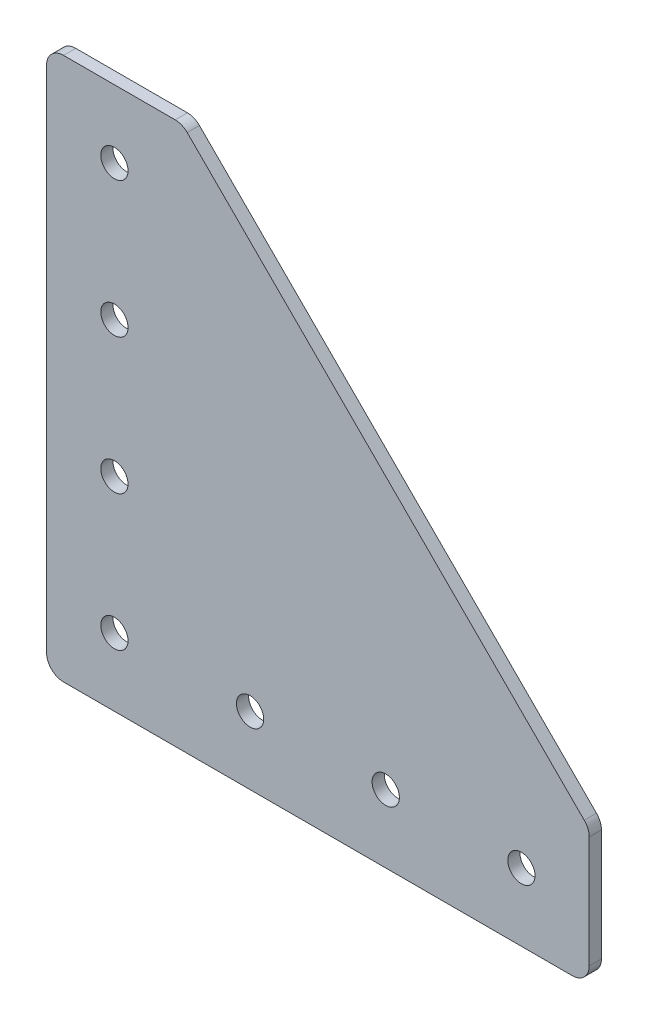
SolidWorks part; units mm, degrees
ref_plane "Front Plane" through (0, 0, 0) normal (0, 0, 1) x (1, 0, 0)
ref_plane "Top Plane" through (0, 0, 0) normal (0, 1, 0) x (1, 0, 0)
ref_plane "Right Plane" through (0, 0, 0) normal (1, 0, 0) x (0, 0, -1)
sketch "Sketch1" plane through (0, 0, 0) normal (0, 0, 1) x (1, 0, 0)
  line L0 (43.0463, -67.5105) -> (43.0463, -42.1105)
  line L1 (-58.5537, 34.0895) -> (-33.1537, 34.0895)
  line L2 (-58.5537, 34.0895) -> (-58.5537, -67.5105)
  line L3 (-58.5537, -67.5105) -> (43.0463, -67.5105)
  line L4 (-45.8537, 34.0895) -> (-45.8537, -67.5105) construction
  line L5 (0, 0) -> (38.8723, -37.9365) construction
  line L6 (-58.5537, -67.5105) -> (0.4347, 0.5011) construction
  line L7 (43.0463, -42.1105) -> (-33.1537, 34.0895)
  circle A0 centre (-45.8537, 21.3895) radius 2.5527
  circle A1 centre (-45.8537, -4.0105) radius 2.5527
  circle A2 centre (-45.8537, -29.4105) radius 2.5527
  circle A3 centre (-45.8537, -54.8105) radius 2.5527
  circle A4 centre (-20.4537, -54.8105) radius 2.5527
  circle A5 centre (4.9463, -54.8105) radius 2.5527
  circle A6 centre (30.3463, -54.8105) radius 2.5527
  point P0 (0, 0)
  dimension "D8" = 5.1054
  dimension "D1" = 25.4
  dimension "D2" = 25.4
  dimension "D3" = 101.6
  dimension "D4" = 101.6
  dimension "D5" = 12.7
  dimension "D6" = 4
  dimension "D7" = 4
extrude "Boss-Extrude1" add sketch "Sketch1" along normal mid plane 2.286
fillet "Fillet1" radius 3.175 5 edges at (-58.5537, 34.0895, 0) (43.0463, -42.1105, 0) (43.0463, -67.5105, 0) (-58.5537, -67.5105, 0) (-33.1537, 34.0895, 0)
